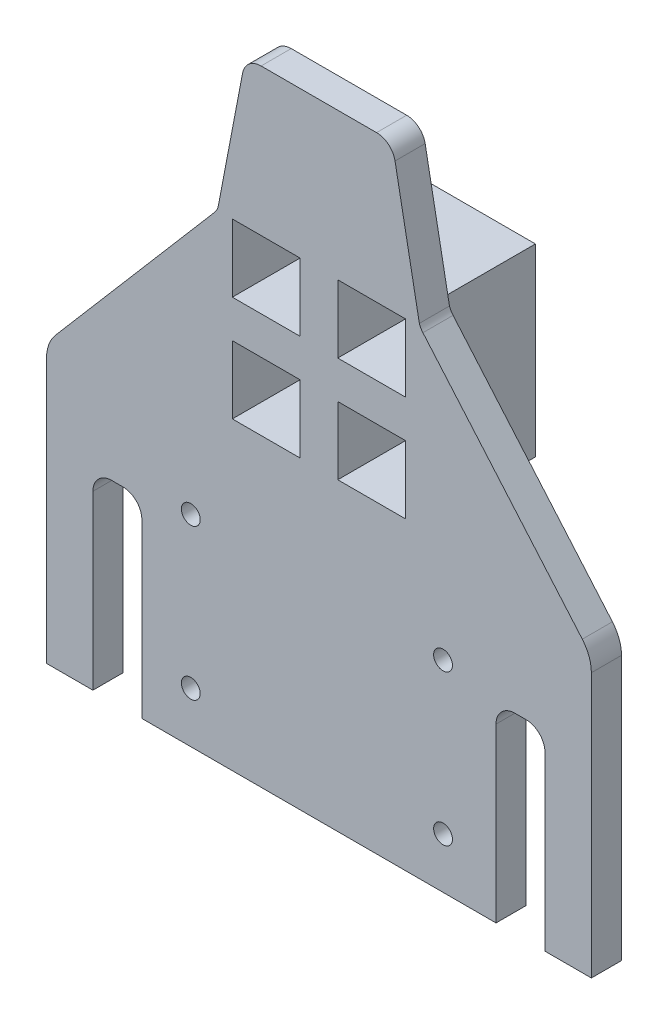
SolidWorks part; units mm, degrees
ref_plane "Front Plane" through (0, 0, 0) normal (0, 0, 1) x (1, 0, 0)
ref_plane "Top Plane" through (0, 0, 0) normal (0, 1, 0) x (1, 0, 0)
ref_plane "Right Plane" through (0, 0, 0) normal (1, 0, 0) x (0, 0, -1)
sketch "Sketch1" plane through (0, 0, 0) normal (0, 0, 1) x (1, 0, 0)
  line L4 (70, 309.9858) -> (85.2992, 309.9858)
  line L6 (43.2101, 271.7903) -> (49.7246, 305.9232)
  line L7 (42.2614, 270.1156) -> (0.0495, 220.7861)
  line L8 (0.0495, 220.7861) -> (42.9, 220.7861) construction
  line L9 (42.9, 220.7861) -> (42.9, 270.8599) construction
  line L10 (96.9829, 220.8599) -> (96.9829, 270.8599) construction
  line L11 (112.4871, 25.7747) -> (89.3829, 25.7747) construction
  line L12 (27.5129, 25.7747) -> (50.5, 25.7747) construction
  line L13 (25.2828, 25.7823) -> (2.6386, 25.8599)
  line L14 (96.6727, 271.7903) -> (90.212, 305.9159)
  line L15 (70, 329.5221) -> (70, -78.2612) construction
  line L18 (50.5, 25.7747) -> (50.5, 0) construction
  line L19 (70, 309.9858) -> (54.636, 309.9858)
  line L20 (135.9829, 220.8599) -> (96.9829, 220.8599) construction
  line L21 (139.9505, 220.7861) -> (135.9829, 220.8599) construction
  line L25 (89.3829, 25.7747) -> (89.3829, 0) construction
  line L27 (89.3829, 0) -> (50.5, 0)
  line L28 (15.2188, 54.8072) -> (17.7021, 54.8072)
  line L35 (125.0395, 54.8072) -> (122.0396, 54.8072)
  line L36 (122.0396, 194.8072) -> (125.0395, 194.8072)
  line L37 (117.0396, 59.8072) -> (117.0396, 189.8072)
  line L38 (130.0395, 189.8072) -> (130.0395, 59.8072)
  line L39 (142.3614, 214.274) -> (142.3614, 30.8599)
  line L40 (97.6215, 270.1156) -> (139.9505, 220.7861)
  line L41 (-2.3614, 214.274) -> (-2.3614, 30.8599)
  line L42 (9.9605, 189.8072) -> (9.9605, 60.0656)
  line L43 (22.9604, 60.0656) -> (22.9604, 189.8072)
  line L44 (17.9604, 194.8072) -> (14.9605, 194.8072)
  line L45 (28.9972, 24.1103) -> (50.5, 0)
  line L46 (114.7172, 25.7823) -> (137.3614, 25.8599)
  line L47 (89.3829, 0) -> (111.0028, 24.1103)
  arc A1 (42.2614, 270.1156) -> (43.2101, 271.7903) centre (38.4667, 273.3715) ccw
  arc A5 (97.6215, 270.1156) -> (96.6727, 271.7903) centre (101.4161, 273.3715) cw
  arc A8 (137.3614, 25.8599) -> (142.3614, 30.8599) centre (137.3614, 30.8599) ccw
  arc A9 (2.6386, 25.8599) -> (-2.3614, 30.8599) centre (2.6386, 30.8599) cw
  arc A10 (49.7246, 305.9232) -> (54.636, 309.9858) centre (54.636, 304.9858) cw
  arc A11 (85.2992, 309.9858) -> (90.212, 305.9159) centre (85.2992, 304.9858) cw
  arc A12 (139.9505, 220.7861) -> (142.3614, 214.274) centre (132.3614, 214.274) cw
  arc A13 (0.0495, 220.7861) -> (-2.3614, 214.274) centre (7.6386, 214.274) ccw
  arc A14 (25.2828, 25.7823) -> (28.9972, 24.1103) centre (25.2657, 20.7823) cw
  arc A15 (114.7172, 25.7823) -> (111.0028, 24.1103) centre (114.7343, 20.7823) ccw
  arc A16 (17.9604, 194.8072) -> (22.9604, 189.8072) centre (17.9604, 189.8072) cw
  arc A17 (9.9605, 189.8072) -> (14.9605, 194.8072) centre (14.9605, 189.8072) cw
  arc A18 (125.0395, 54.8072) -> (130.0395, 59.8072) centre (125.0395, 59.8072) ccw
  arc A19 (122.0396, 54.8072) -> (117.0396, 59.8072) centre (122.0396, 59.8072) cw
  arc A20 (125.0395, 194.8072) -> (130.0395, 189.8072) centre (125.0395, 189.8072) cw
  arc A21 (117.0396, 189.8072) -> (122.0396, 194.8072) centre (122.0396, 189.8072) cw
  arc A22 (17.7021, 54.8072) -> (22.9604, 60.0656) centre (17.7021, 60.0656) ccw
  arc A23 (15.2188, 54.8072) -> (9.9605, 60.0656) centre (15.2188, 60.0656) cw
  point P18 (22.9604, 194.8072)
  point P51 (9.9605, 194.8072)
  point P57 (130.0395, 54.8072)
  point P61 (117.0396, 54.8072)
  point P67 (130.0395, 194.8072)
  point P70 (117.0396, 194.8072)
  point P77 (22.9604, 54.8072)
  point P80 (9.9605, 54.8072)
  dimension "D1" = 5
  dimension "D2" = 5
  dimension "D3" = 5
  dimension "D4" = 10
  dimension "D5" = 5
  dimension "D6" = 5
  dimension "D7" = 5.2583
extrude "Boss-Extrude1" add sketch "Sketch1" along normal blind 8
sketch "Sketch3" plane through (0, 0, 0) normal (0, 0, -1) x (-1, 0, 0)
  line L1 (-142.3614, 144.0523) -> (2.3614, 144.0523)
  line L3 (-142.3614, 30.8599) -> (-142.3614, 214.274) construction
  line L6 (2.3614, 214.274) -> (2.3614, 30.8599) construction
split "Split1" trim tools "Sketch3" bodies to split 101 resulting bodies 104 108
ref_plane "Plane4" through (0, 144.0523, 0) normal (0, 1, 0) x (1, 0, 0)
sketch "Sketch4" plane through (0, 144.0523, 0) normal (0, -1, 0) x (-1, 0, 0)
  line L0 (-3.7995, -8) -> (-3.7995, -4)
  line L2 (2.3614, -8) -> (-9.9605, -8) construction
  circle A1 centre (-70, -4) radius 2.5
  circle A2 centre (-40, -4) radius 2.5
  circle A3 centre (-100, -4) radius 2.5
  circle A5 centre (-137.3614, -4) radius 2.5
  circle A6 centre (-3.7995, -4) radius 2.5
sketch "Sketch5" plane through (0, 144.0523, -115.3599) normal (0, -1, 0) x (1, 0, 0)
  circle A1 centre (70, 119.3599) radius 2.5
  circle A2 centre (100, 119.3599) radius 2.5
  circle A3 centre (40, 119.3599) radius 2.5
  circle A5 centre (2.6386, 119.3599) radius 2.5
  circle A6 centre (137.3614, 119.3599) radius 2.5
extrude "Cut-Extrude6" cut sketch "Sketch5" along direction (0, -1, 0) on the side of the normal blind 5.2 contours A5 | A3 | A1
extrude "Cut-Extrude7" cut sketch "Sketch4" against normal blind 10
delete or keep bodies "Body-Delete/Keep 3" type delete bodies bodies 106
sketch "Sketch6" plane through (0, 0, 8) normal (0, 0, 1) x (1, 0, 0)
  circle A0 centre (50.0001, 267.9803) radius 1.5
  circle A1 centre (90.0001, 267.9803) radius 1.5
  circle A2 centre (90.0001, 227.9803) radius 1.5
  circle A3 centre (50.0001, 227.9803) radius 1.5
extrude "Cut-Extrude8" cut sketch "Sketch6" against normal through all
sketch "Sketch7" plane through (0, 0, 0) normal (0, 0, -1) x (-1, 0, 0)
  line L10 (-94.5001, 223.4803) -> (-94.5001, 272.4803)
  line L11 (-47.0001, 270.9803) -> (-47.0001, 252.9803)
  line L12 (-45.5001, 272.4803) -> (-45.5001, 223.4803)
  line L13 (-45.5001, 223.4803) -> (-94.5001, 223.4803)
  line L14 (-93.0001, 270.9803) -> (-75.0001, 270.9803)
  line L15 (-93.0001, 224.9803) -> (-75.0001, 224.9803)
  line L16 (-93.0001, 224.9803) -> (-93.0001, 242.9803)
  line L18 (-65.0001, 270.9803) -> (-65.0001, 252.9803)
  line L19 (-65.0001, 224.9803) -> (-47.0001, 224.9803)
  line L20 (-45.5001, 272.4803) -> (-94.5001, 272.4803)
  line L21 (-75.0001, 270.9803) -> (-75.0001, 252.9803)
  line L22 (-47.0001, 252.9803) -> (-65.0001, 252.9803)
  line L23 (-47.0001, 242.9803) -> (-47.0001, 224.9803)
  line L24 (-93.0001, 242.9803) -> (-75.0001, 242.9803)
  line L25 (-65.0001, 270.9803) -> (-47.0001, 270.9803)
  line L26 (-75.0001, 252.9803) -> (-93.0001, 252.9803)
  line L27 (-65.0001, 242.9803) -> (-47.0001, 242.9803)
  line L28 (-65.0001, 242.9803) -> (-65.0001, 224.9803)
  line L29 (-75.0001, 242.9803) -> (-75.0001, 224.9803)
  line L30 (-93.0001, 252.9803) -> (-93.0001, 270.9803)
extrude "Boss-Extrude2" add sketch "Sketch7" along normal blind 15
sketch "Sketch8" plane through (0, 0, -15) normal (0, 0, -1) x (-1, 0, 0)
  line L0 (-45.5001, 272.4803) -> (-94.5001, 272.4803)
  line L1 (-94.5001, 272.4803) -> (-94.5001, 223.4803)
  line L2 (-94.5001, 223.4803) -> (-45.5001, 223.4803)
  line L3 (-94.5001, 223.4803) -> (-45.5001, 223.4803) construction
  line L4 (-94.5001, 223.4803) -> (-45.5001, 223.4803) construction
  line L5 (-45.5001, 223.4803) -> (-45.5001, 272.4803)
  circle A0 centre (-50.0001, 267.9803) radius 1.5
  circle A1 centre (-90.0001, 267.9803) radius 1.5
  circle A2 centre (-50.0001, 227.9803) radius 1.5
  circle A3 centre (-90.0001, 227.9803) radius 1.5
extrude "Boss-Extrude3" add sketch "Sketch8" along normal blind 10
sketch "Sketch9" plane through (0, 0, 8) normal (0, 0, 1) x (1, 0, 0)
  line L9 (45.5001, 272.4803) -> (94.5001, 272.4803)
  line L10 (45.5001, 272.4803) -> (45.5001, 223.4803)
  line L11 (45.5001, 223.4803) -> (94.5001, 223.4803)
  line L12 (94.5001, 272.4803) -> (94.5001, 223.4803)
extrude "Cut-Extrude9" cut sketch "Sketch9" against normal blind 8
sketch "Sketch10" plane through (0, 0, 0) normal (0, 0, 1) x (1, 0, 0)
  line L17 (94.5001, 223.4803) -> (45.5001, 223.4803)
  line L18 (45.5001, 223.4803) -> (45.5001, 224.9803)
  line L19 (45.5001, 272.4803) -> (45.5001, 223.4803) construction
  line L23 (47.0001, 242.9803) -> (65.0001, 242.9803)
  line L24 (47.0001, 242.9803) -> (47.0001, 224.9803)
  line L26 (47.0001, 224.9803) -> (65.0001, 224.9803)
  line L27 (65.0001, 242.9803) -> (65.0001, 224.9803)
  line L29 (45.5001, 223.4803) -> (45.5001, 272.4803) construction
  line L30 (45.5001, 242.9803) -> (45.5001, 224.9803)
  line L31 (45.5001, 272.4803) -> (94.5001, 272.4803)
  line L32 (94.5001, 272.4803) -> (94.5001, 223.4803)
  line L40 (75.0001, 242.9803) -> (93.0001, 242.9803)
  line L41 (75.0001, 242.9803) -> (75.0001, 224.9803)
  line L42 (75.0001, 224.9803) -> (93.0001, 224.9803)
  line L43 (93.0001, 242.9803) -> (93.0001, 224.9803)
  line L44 (75.0001, 270.9803) -> (93.0001, 270.9803)
  line L45 (75.0001, 270.9803) -> (75.0001, 252.9803)
  line L46 (75.0001, 252.9803) -> (93.0001, 252.9803)
  line L47 (93.0001, 270.9803) -> (93.0001, 252.9803)
  line L48 (47.0001, 270.9803) -> (65.0001, 270.9803)
  line L49 (47.0001, 270.9803) -> (47.0001, 252.9803)
  line L50 (47.0001, 252.9803) -> (65.0001, 252.9803)
  line L51 (65.0001, 270.9803) -> (65.0001, 252.9803)
  line M21 (93.0001, 224.9803) -> (75.0001, 224.9803)
  line M22 (75.0001, 224.9803) -> (75.0001, 242.9803)
  line M23 (75.0001, 242.9803) -> (93.0001, 242.9803)
  line M24 (93.0001, 242.9803) -> (93.0001, 224.9803)
  line M25 (65.0001, 224.9803) -> (47.0001, 224.9803)
  line M26 (47.0001, 224.9803) -> (47.0001, 242.9803)
  line M27 (47.0001, 242.9803) -> (65.0001, 242.9803)
  line M28 (65.0001, 242.9803) -> (65.0001, 224.9803)
  line M29 (65.0001, 270.9803) -> (65.0001, 252.9803)
  line M30 (65.0001, 252.9803) -> (47.0001, 252.9803)
  line M31 (47.0001, 252.9803) -> (47.0001, 270.9803)
  line M32 (47.0001, 270.9803) -> (65.0001, 270.9803)
  line M33 (93.0001, 252.9803) -> (75.0001, 252.9803)
  line M34 (75.0001, 252.9803) -> (75.0001, 270.9803)
  line M35 (75.0001, 270.9803) -> (93.0001, 270.9803)
  line M36 (93.0001, 270.9803) -> (93.0001, 252.9803)
  line M37 (45.5001, 272.4803) -> (45.5001, 223.4803)
  line M38 (45.5001, 223.4803) -> (94.5001, 223.4803)
  line M39 (94.5001, 223.4803) -> (94.5001, 272.4803)
  line M40 (94.5001, 272.4803) -> (45.5001, 272.4803)
extrude "Boss-Extrude4" add sketch "Sketch10" along normal blind 8 contours M40 M37 M38 M39 M36 M33 M34 M35 M32 M29 M30 M31 M28 M25 M26 M27 M24 M21 M22 M23
sketch "Sketch12" plane through (0, 0, 0) normal (0, 0, -1) x (-1, 0, 0)
  circle A0 centre (-102.9604, 197.5034) radius 2.5
  circle A1 centre (-35.9604, 197.5034) radius 2.5
  circle A2 centre (-35.9604, 157.5034) radius 2.5
  circle A3 centre (-102.9604, 157.5034) radius 2.5
extrude "Cut-Extrude10" cut sketch "Sketch12" against normal through all
